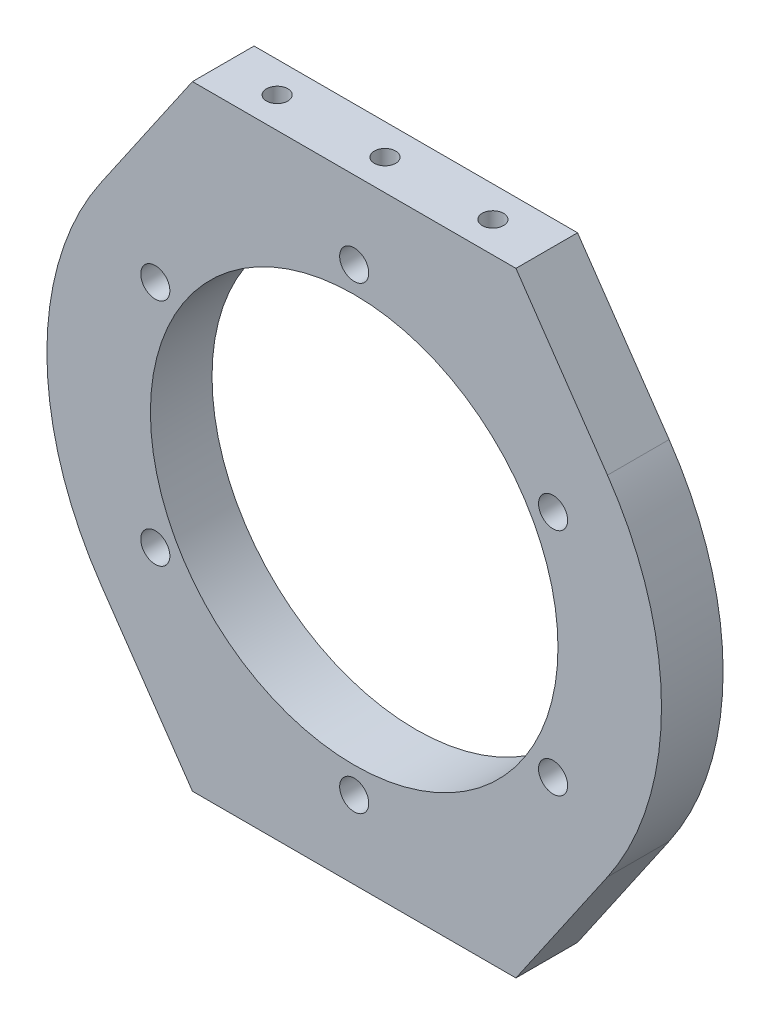
SolidWorks part; units mm, degrees
ref_plane "Front Plane" through (0, 0, 0) normal (0, 0, 1) x (1, 0, 0)
ref_plane "Top Plane" through (0, 0, 0) normal (0, 1, 0) x (1, 0, 0)
ref_plane "Right Plane" through (0, 0, 0) normal (1, 0, 0) x (0, 0, -1)
sketch "Sketch1" plane through (0, 0, 0) normal (0, 0, 1) x (1, 0, 0)
  line L0 (0, 52) -> (0, -52) construction
  line L1 (-47.5, 0) -> (47.5, 0) construction
  line L2 (-25, 47.5) -> (25, 47.5)
  line L3 (-39.154, 26.8926) -> (-25, 47.5)
  line L4 (0, 52) -> (0, 47.5) construction
  line L5 (39.154, 26.8926) -> (25, 47.5)
  line L6 (39.154, -26.8926) -> (25, -47.5)
  line L7 (-25, -47.5) -> (25, -47.5)
  line L8 (-39.154, -26.8926) -> (-25, -47.5)
  arc A0 (-39.154, 26.8926) -> (-39.154, -26.8926) centre (0, 0) ccw
  arc A1 (39.154, -26.8926) -> (39.154, 26.8926) centre (0, 0) ccw
  dimension "D1" = 95
  dimension "D2" = 50
  dimension "D3" = 47.5
extrude "Boss-Extrude1" add sketch "Sketch1" against normal blind 9.525
sketch "Sketch2" plane through (0, 0, 0) normal (0, 0, 1) x (1, 0, 0)
  circle A2 centre (0, 0) radius 35.5 construction
  point P93 (0, 35.5)
  point P95 (59.233, 29.0385)
  point P98 (0, 35.5)
  point P105 (30.7439, 17.75)
  point P106 (30.7439, -17.75)
  point P107 (0, -35.5)
  point P108 (-30.7439, -17.75)
  point P109 (-30.7439, 17.75)
  dimension "D1" = 71
hole_wizard "M4 Clearance Hole1" positions "Sketch2" profile "Sketch3" hole size "M4" standard "ANSI Metric" end condition through all
sketch "Sketch3" plane through (-30.7439, 17.75, 0) normal (1, 0, 0) x (0, -1, 0)
  line L0 (0, 0) -> (0, 9.525)
  line L1 (0, 9.525) -> (2.25, 9.525)
  line L2 (2.25, 9.525) -> (2.25, 0)
  line L5 (2.25, 0) -> (0, 0)
  line L11 (0, -6.35) -> (0, 107.95) construction
  dimension "Thru Hole Dia." = 4.5
  dimension "Thru Hole Depth" = 9.525
sketch "Sketch4" plane through (0, 0, -9.525) normal (0, 0, -1) x (-1, 0, 0)
  circle A0 centre (0, 0) radius 31.5
  dimension "D1" = 63
extrude "Cut-Extrude1" cut sketch "Sketch4" against normal through all
sketch "Sketch5" plane through (0, -47.5, 0) normal (0, -1, 0) x (1, 0, 0)
  point P0 (0, -4.7625)
  point P1 (16.67, -4.7625)
  point P2 (-16.67, -4.7625)
  dimension "D1" = 4.7625
  dimension "D2" = 16.67
  dimension "D3" = 16.67
sketch "Sketch6" plane through (0, 47.5, 0) normal (0, 1, 0) x (1, 0, 0)
  point P0 (16.67, 4.7625)
  point P2 (0, 4.7625)
  point P4 (-16.67, 4.7625)
hole_wizard "M4x0.7 Tapped Hole1" positions "Sketch6" profile "Sketch7" tap size "M4x0.7" standard "ANSI Metric"
sketch "Sketch7" plane through (16.67, 47.5, -4.7625) normal (1, 0, 0) x (0, 0, 1)
  line L0 (0, 0) -> (0, 10.9914)
  line L1 (0, 10.9914) -> (1.65, 10)
  line L2 (1.65, 10) -> (1.65, 0)
  line L5 (1.65, 0) -> (0, 0)
  line L10 (0, 10.9914) -> (-1.65, 10) construction
  line L11 (0, -6.35) -> (0, 107.95) construction
  dimension "Tap Drill Dia." = 3.3
  dimension "Tap Drill Depth" = 10
  dimension "Drill Angle" = 118
hole_wizard "M4x0.7 Tapped Hole2" positions "Sketch5" profile "Sketch8" tap size "M4x0.7" standard "ANSI Metric"
sketch "Sketch8" plane through (0, -47.5, -4.7625) normal (1, 0, 0) x (0, 0, -1)
  line L0 (0, 0) -> (0, 10.9914)
  line L1 (0, 10.9914) -> (1.65, 10)
  line L2 (1.65, 10) -> (1.65, 0)
  line L5 (1.65, 0) -> (0, 0)
  line L10 (0, 10.9914) -> (-1.65, 10) construction
  line L11 (0, -6.35) -> (0, 107.95) construction
  dimension "Tap Drill Dia." = 3.3
  dimension "Tap Drill Depth" = 10
  dimension "Drill Angle" = 118
